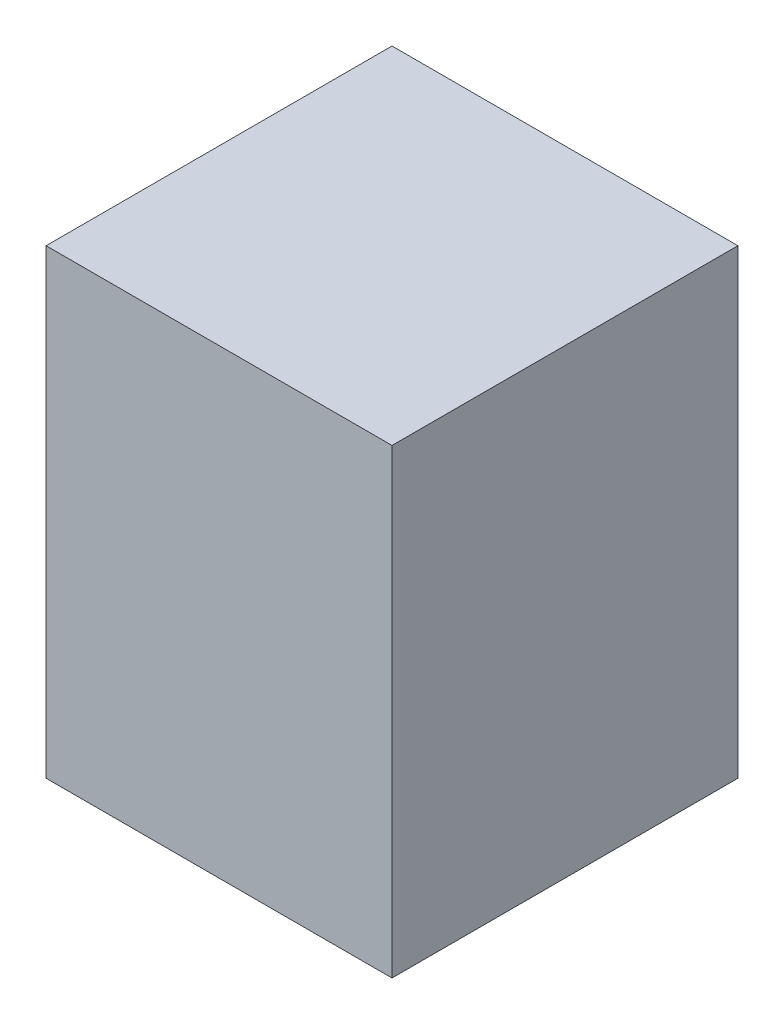
SolidWorks part; units mm, degrees
ref_plane "Front" through (0, 0, 0) normal (0, 0, 1) x (1, 0, 0)
ref_plane "Top" through (0, 0, 0) normal (0, 1, 0) x (1, 0, 0)
ref_plane "Right" through (0, 0, 0) normal (1, 0, 0) x (0, 0, -1)
sketch "Эскиз1" plane through (0, 0, 0) normal (0, 1, 0) x (1, 0, 0)
  line L1 (0, 0) -> (6, 0)
  line L2 (0, 0) -> (0, -6)
  line L3 (0, -6) -> (6, -6)
  line L4 (6, 0) -> (6, -6)
  dimension "D1" = 6
  dimension "D2" = 6
extrude "Бобышка-Вытянуть1" add sketch "Эскиз1" along normal blind 8
